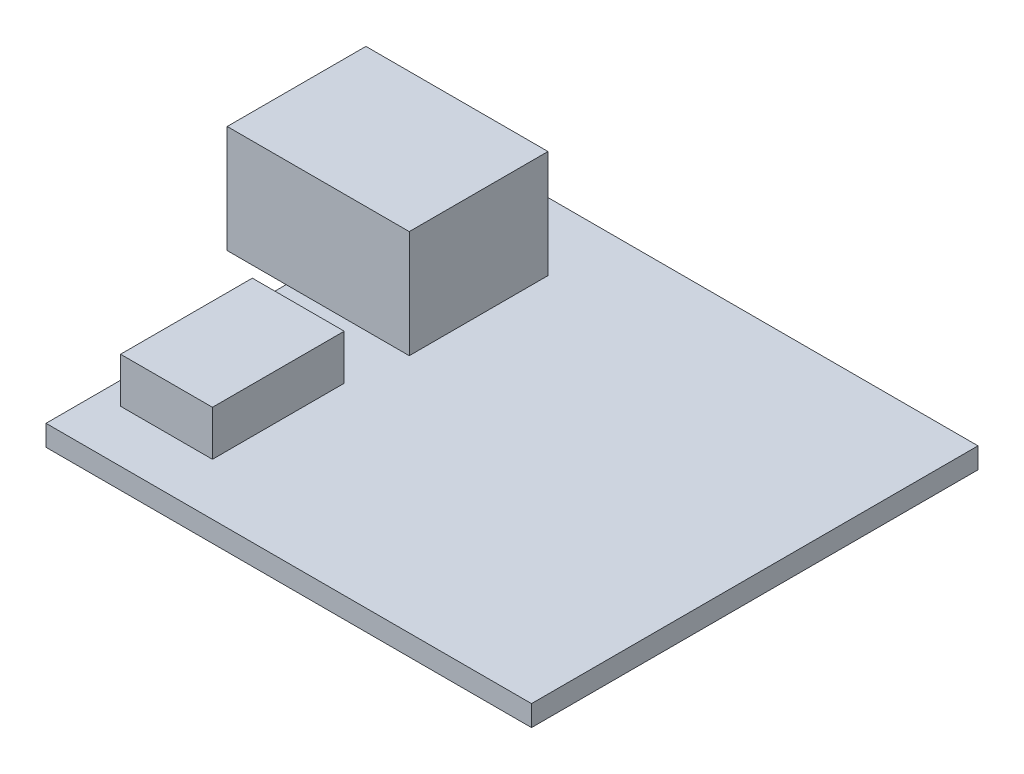
SolidWorks part; units mm, degrees
ref_plane "Front Plane" through (0, 0, 0) normal (0, 0, 1) x (1, 0, 0)
ref_plane "Top Plane" through (0, 0, 0) normal (0, 1, 0) x (1, 0, 0)
ref_plane "Right Plane" through (0, 0, 0) normal (1, 0, 0) x (0, 0, -1)
sketch "Sketch1" plane through (0, 0, 0) normal (0, 1, 0) x (1, 0, 0)
  line L1 (-14, -12.875) -> (14, -12.875)
  line L2 (-14, -12.875) -> (-14, 12.875)
  line L3 (-14, 12.875) -> (14, 12.875)
  line L4 (14, -12.875) -> (14, 12.875)
  line L5 (-14, -12.875) -> (14, 12.875) construction
  line L6 (-14, 12.875) -> (14, -12.875) construction
  point P0 (0, 0)
  dimension "D1" = 28
  dimension "D2" = 25.75
extrude "Boss-Extrude1" add sketch "Sketch1" along normal blind 1.2
sketch "Sketch2" plane through (0, 1.2, 0) normal (0, 1, 0) x (1, 0, 0)
  line L0 (-14, 12.875) -> (-14, -12.875) construction
  line L1 (-6.9, 8.975) -> (-17.4, 8.975)
  line L2 (-6.9, 8.975) -> (-6.9, 0.975)
  line L3 (-6.9, 0.975) -> (-17.4, 0.975)
  line L4 (-17.4, 8.975) -> (-17.4, 0.975)
  line L5 (14, 12.875) -> (-14, 12.875) construction
  dimension "D1" = 8
  dimension "D2" = 10.5
  dimension "D3" = 3.4
  dimension "D4" = 3.9
extrude "Boss-Extrude2" add sketch "Sketch2" along normal blind 6.2
sketch "Sketch3" plane through (0, 1.2, 0) normal (0, 1, 0) x (1, 0, 0)
  line L0 (-14, -12.875) -> (14, -12.875) construction
  line L1 (-7.4, -2.275) -> (-12.7, -2.275)
  line L2 (-7.4, -2.275) -> (-7.4, -9.875)
  line L3 (-7.4, -9.875) -> (-12.7, -9.875)
  line L4 (-12.7, -2.275) -> (-12.7, -9.875)
  line L5 (-14, 0.975) -> (-14, -12.875) construction
  dimension "D1" = 7.6
  dimension "D2" = 5.3
  dimension "D3" = 3
  dimension "D4" = 1.3
extrude "Boss-Extrude3" add sketch "Sketch3" along normal blind 2.6
